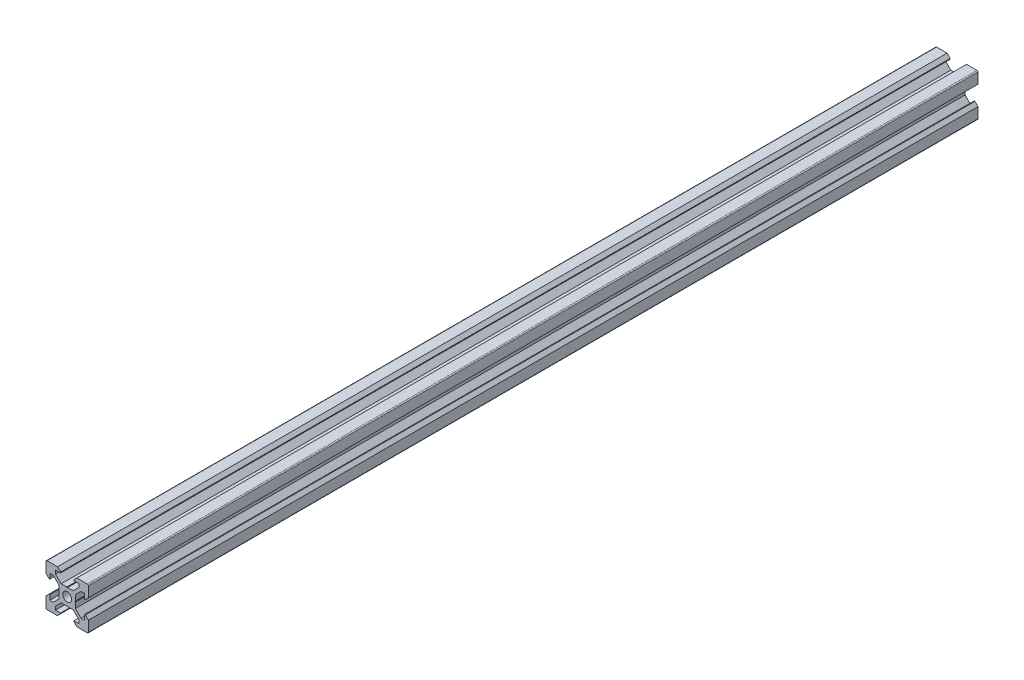
SolidWorks part; units mm, degrees
material "6061-T6 (SS)"
ref_plane "Front Plane" through (0, 0, 0) normal (0, 0, 1) x (1, 0, 0)
ref_plane "Top Plane" through (0, 0, 0) normal (0, 1, 0) x (1, 0, 0)
ref_plane "Right Plane" through (0, 0, 0) normal (1, 0, 0) x (0, 0, -1)
sketch "Sketch1" plane through (0, 0, 0) normal (0, 0, 1) x (1, 0, 0)
  line L1 (9.5, -10) -> (-9.5, -10)
  line L2 (10, -9.5) -> (10, 9.5)
  line L3 (9.5, 10) -> (-9.5, 10)
  line L4 (-10, -9.5) -> (-10, 9.5)
  line L5 (10, -10) -> (-10, 10) construction
  line L6 (10, 10) -> (-10, -10) construction
  circle A0 centre (0, 0) radius 2.1
  arc A1 (-9.5, 10) -> (-10, 9.5) centre (-9.5, 9.5) ccw
  arc A2 (10, 9.5) -> (9.5, 10) centre (9.5, 9.5) ccw
  arc A3 (9.5, -10) -> (10, -9.5) centre (9.5, -9.5) ccw
  arc A4 (-9.5, -10) -> (-10, -9.5) centre (-9.5, -9.5) cw
  point P0 (0, 0)
  line B0 (0, 0) -> (0, 10) construction
  line B1 (0, 3.69) -> (-0.21, 3.9)
  line B2 (-0.21, 3.9) -> (-2.8393, 3.9)
  line B3 (-2.8393, 3.9) -> (-5.5, 6.5607)
  line B4 (-5.5, 6.5607) -> (-5.5, 8.2)
  line B5 (-5.5, 8.2) -> (-3.125, 8.2)
  line B6 (-3.125, 8.2) -> (-3.125, 8.545)
  line B7 (-3.125, 8.545) -> (-4.58, 10)
  line B8 (-4.58, 10) -> (4.58, 10)
  line B9 (0, 0) -> (-5.9132, 5.9132) construction
  line B10 (3.125, 8.545) -> (4.58, 10)
  line B11 (3.125, 8.2) -> (3.125, 8.545)
  line B12 (5.5, 8.2) -> (3.125, 8.2)
  line B13 (5.5, 6.5607) -> (5.5, 8.2)
  line B14 (2.8393, 3.9) -> (5.5, 6.5607)
  line B15 (0.21, 3.9) -> (2.8393, 3.9)
  line B16 (0, 3.69) -> (0.21, 3.9)
  line B17 (0, 0) -> (-10, 0) construction
  line B18 (-3.69, 0) -> (-3.9, -0.21)
  line B19 (-3.9, -0.21) -> (-3.9, -2.8393)
  line B20 (-3.9, -2.8393) -> (-6.5607, -5.5)
  line B21 (-6.5607, -5.5) -> (-8.2, -5.5)
  line B22 (-8.2, -5.5) -> (-8.2, -3.125)
  line B23 (-8.2, -3.125) -> (-8.545, -3.125)
  line B24 (-8.545, -3.125) -> (-10, -4.58)
  line B25 (-10, -4.58) -> (-10, 4.58)
  line B26 (0, 0) -> (-5.9132, -5.9132) construction
  line B27 (-8.545, 3.125) -> (-10, 4.58)
  line B28 (-8.2, 3.125) -> (-8.545, 3.125)
  line B29 (-8.2, 5.5) -> (-8.2, 3.125)
  line B30 (-6.5607, 5.5) -> (-8.2, 5.5)
  line B31 (-3.9, 2.8393) -> (-6.5607, 5.5)
  line B32 (-3.9, 0.21) -> (-3.9, 2.8393)
  line B33 (-3.69, 0) -> (-3.9, 0.21)
  line B34 (0, 0) -> (0, -10) construction
  line B35 (0, -3.69) -> (0.21, -3.9)
  line B36 (0.21, -3.9) -> (2.8393, -3.9)
  line B37 (2.8393, -3.9) -> (5.5, -6.5607)
  line B38 (5.5, -6.5607) -> (5.5, -8.2)
  line B39 (5.5, -8.2) -> (3.125, -8.2)
  line B40 (3.125, -8.2) -> (3.125, -8.545)
  line B41 (3.125, -8.545) -> (4.58, -10)
  line B42 (4.58, -10) -> (-4.58, -10)
  line B43 (0, 0) -> (5.9132, -5.9132) construction
  line B44 (-3.125, -8.545) -> (-4.58, -10)
  line B45 (-3.125, -8.2) -> (-3.125, -8.545)
  line B46 (-5.5, -8.2) -> (-3.125, -8.2)
  line B47 (-5.5, -6.5607) -> (-5.5, -8.2)
  line B48 (-2.8393, -3.9) -> (-5.5, -6.5607)
  line B49 (-0.21, -3.9) -> (-2.8393, -3.9)
  line B50 (0, -3.69) -> (-0.21, -3.9)
  line B51 (0, 0) -> (10, 0) construction
  line B52 (3.69, 0) -> (3.9, 0.21)
  line B53 (3.9, 0.21) -> (3.9, 2.8393)
  line B54 (3.9, 2.8393) -> (6.5607, 5.5)
  line B55 (6.5607, 5.5) -> (8.2, 5.5)
  line B56 (8.2, 5.5) -> (8.2, 3.125)
  line B57 (8.2, 3.125) -> (8.545, 3.125)
  line B58 (8.545, 3.125) -> (10, 4.58)
  line B59 (10, 4.58) -> (10, -4.58)
  line B60 (0, 0) -> (5.9132, 5.9132) construction
  line B61 (8.545, -3.125) -> (10, -4.58)
  line B62 (8.2, -3.125) -> (8.545, -3.125)
  line B63 (8.2, -5.5) -> (8.2, -3.125)
  line B64 (6.5607, -5.5) -> (8.2, -5.5)
  line B65 (3.9, -2.8393) -> (6.5607, -5.5)
  line B66 (3.9, -0.21) -> (3.9, -2.8393)
  line B67 (3.69, 0) -> (3.9, -0.21)
  dimension "D1" = 4.2
  dimension "D3" = 0.5
  dimension "D2" = 20
sketch_block_instance "V Slot 1-4"
sketch_block "V Slot 1" parameters "D1"=10, "D2"=11, "D3"=4.3, "D4"=1.8, "D5"=0.21, "D6"=45, "D7"=9.16, "D8"=1.5, "D9"=6.25
sketch_block_instance "V Slot 1-5"
sketch_block_instance "V Slot 1-6"
sketch_block_instance "V Slot 1-7"
extrude "Boss-Extrude1" add sketch "Sketch1" along normal mid plane 420 contours B67 B52 B53 B54 B55 B56 B57 B58 L2 A2 L3 B10 B11 B12 B13 B14 B15 B16 B1 B2 B3 B4 B5 B6 B7 A1 L4 B27 B28 B29 B30 B31 B32 B33 B18 B19 B20 B21 B22 B23 B24 A4 L1 B44 B45 B46 B47 B48 B49
